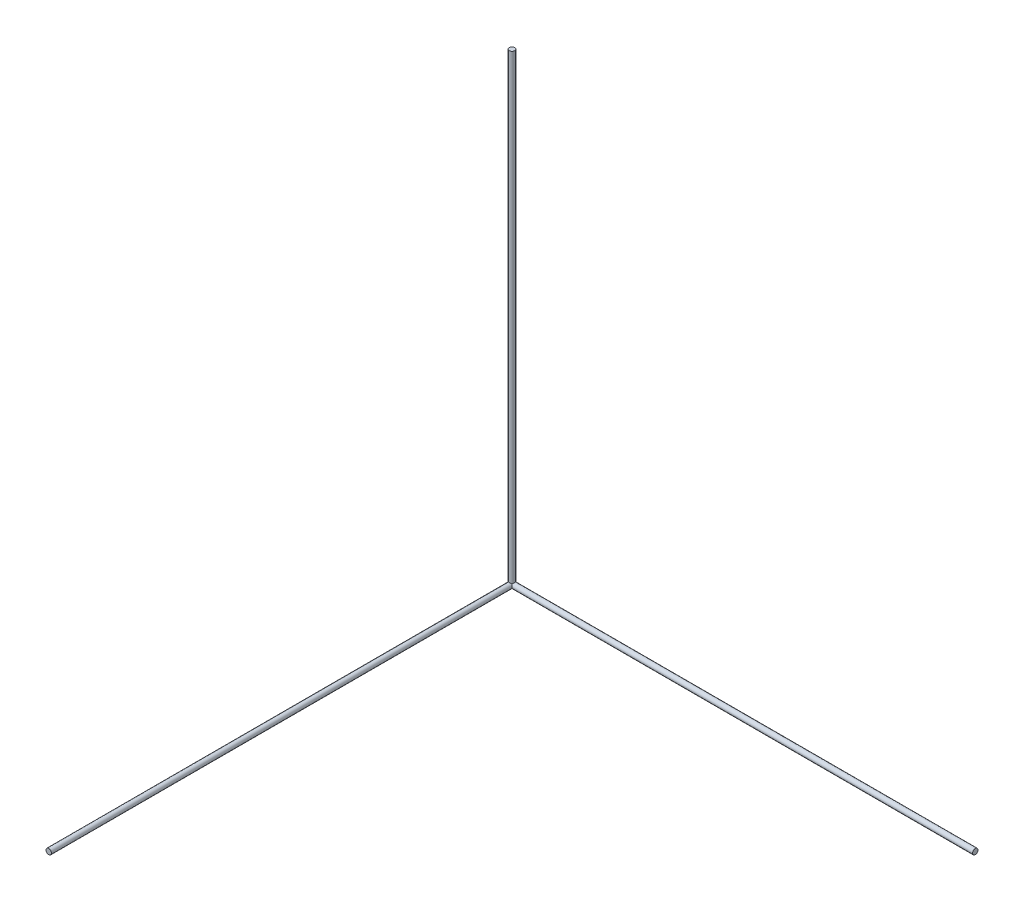
SolidWorks part; units mm, degrees
ref_plane "Front" through (0, 0, 0) normal (0, 0, 1) x (1, 0, 0)
ref_plane "Top" through (0, 0, 0) normal (0, 1, 0) x (1, 0, 0)
ref_plane "Right" through (0, 0, 0) normal (1, 0, 0) x (0, 0, -1)
sketch "Sketch1" plane through (0, 0, 0) normal (0, 0, 1) x (1, 0, 0)
  circle A0 centre (0, 0) radius 1.7656
extrude "Boss-Extrude1" add sketch "Sketch1" along normal blind 300
sketch "Sketch2" plane through (0, 0, 0) normal (1, 0, 0) x (0, 0, -1)
  circle A0 centre (0, 0) radius 1.7656
extrude "Boss-Extrude2" add sketch "Sketch2" along normal blind 300
sketch "Sketch3" plane through (0, 0, 0) normal (0, 1, 0) x (1, 0, 0)
  circle A0 centre (0, 0) radius 1.7656
extrude "Boss-Extrude3" add sketch "Sketch3" along normal blind 300
sketch "Sketch4" plane through (0, 0, 0) normal (0, 1, 0) x (1, 0, 0)
  line L1 (-420.9718, 0.0247) -> (420.9718, 0.0247)
  line L2 (-420.9718, 0.0247) -> (-420.9718, -0.0247)
  line L3 (-420.9718, -0.0247) -> (420.9718, -0.0247)
  line L4 (420.9718, 0.0247) -> (420.9718, -0.0247)
  line L5 (-420.9718, 0.0247) -> (420.9718, -0.0247) construction
  line L6 (-420.9718, -0.0247) -> (420.9718, 0.0247) construction
  point P0 (0, 0)
extrude "Boss-Extrude4" [suppressed] add sketch "Sketch4" along normal mid plane 600
sketch "Sketch6" [suppressed] plane through (0, 0, 0) normal (0, 0, 1) x (1, 0, 0)
  line L0 (420.9718, 300) -> (420.9718, -300) construction
  line L1 (-420.9718, -0.0338) -> (420.9718, -0.0338)
  line L2 (-420.9718, -0.0338) -> (-420.9718, 0.0338)
  line L3 (-420.9718, 0.0338) -> (420.9718, 0.0338)
  line L4 (420.9718, -0.0338) -> (420.9718, 0.0338)
  line L5 (-420.9718, -0.0338) -> (420.9718, 0.0338) construction
  line L6 (-420.9718, 0.0338) -> (420.9718, -0.0338) construction
  point P0 (0, 0)
extrude "Boss-Extrude5" [suppressed] add sketch "Sketch6" along normal mid plane 600
sketch "Sketch9" [suppressed] plane through (0, 0, 0) normal (0, 1, 0) x (1, 0, 0)
  line L0 (420.9718, 300) -> (-420.9718, 300) construction
  line L1 (-0.0017, -300) -> (0.0017, -300)
  line L2 (-0.0017, -300) -> (-0.0017, 300)
  line L3 (-0.0017, 300) -> (0.0017, 300)
  line L4 (0.0017, -300) -> (0.0017, 300)
  line L5 (-0.0017, -300) -> (0.0017, 300) construction
  line L6 (-0.0017, 300) -> (0.0017, -300) construction
  point P0 (0, 0)
extrude "Boss-Extrude7" [suppressed] add sketch "Sketch9" along normal mid plane 600
